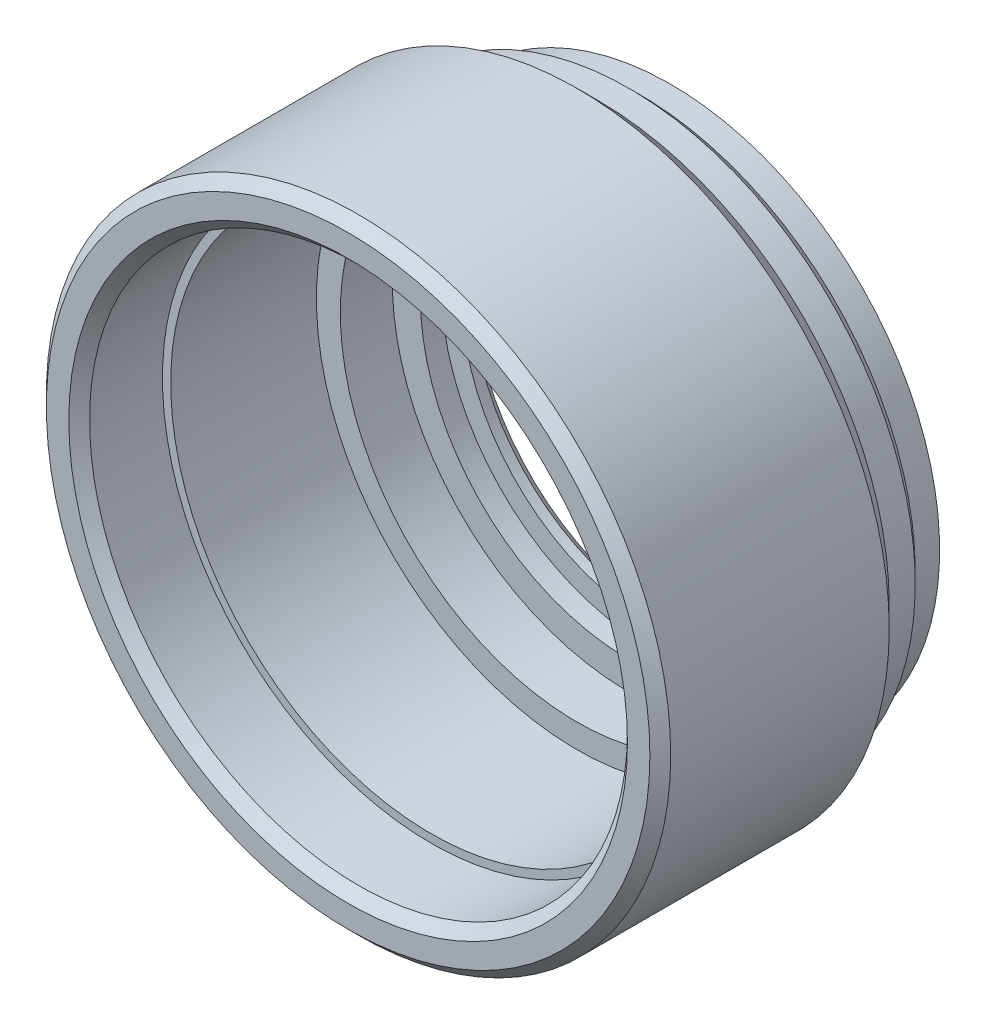
SolidWorks part; units mm, degrees
material "6061 Alloy"
ref_plane "Front Plane" through (0, 0, 0) normal (0, 0, 1) x (1, 0, 0)
ref_plane "Top Plane" through (0, 0, 0) normal (0, 1, 0) x (1, 0, 0)
ref_plane "Right Plane" through (0, 0, 0) normal (1, 0, 0) x (0, 0, -1)
sketch "Sketch1" plane through (0, 0, 0) normal (0, 0, 1) x (1, 0, 0)
  circle A0 centre (0, 0) radius 27.5
  dimension "D1" = 55
extrude "Boss-Extrude1" add sketch "Sketch1" along normal blind 7
sketch "Sketch4" plane through (0, 0, 7) normal (0, 0, 1) x (1, 0, 0)
  circle A0 centre (0, 0) radius 20.05
  dimension "D1" = 40.1
extrude "Cut-Extrude1" cut sketch "Sketch4" against normal offset from surface (5 mm away) 2 up to face at (27.5, 0, 0)
sketch "Sketch5" plane through (0, 0, 2) normal (0, 0, 1) x (1, 0, 0)
  circle A0 centre (0, 0) radius 18.05
  circle A1 centre (0, 0) radius 20.05 construction
  dimension "D1" = 2
extrude "Cut-Extrude2" cut sketch "Sketch5" against normal through all
sketch "Sketch6" plane through (0, 0, 7) normal (0, 0, 1) x (1, 0, 0)
  circle A0 centre (0, 0) radius 20.05
  circle A1 centre (0, 0) radius 30
  circle A2 centre (0, 0) radius 20.05 construction
  dimension "D1" = 60
extrude "Boss-Extrude2" add sketch "Sketch6" along normal blind 24
sketch "Sketch7" plane through (0, 0, 31) normal (0, 0, 1) x (1, 0, 0)
  circle A0 centre (0, 0) radius 25.05
  dimension "D1" = 50.1
extrude "Cut-Extrude3" cut sketch "Sketch7" against normal offset from surface (22 mm away) 2 up to face at (27.5, 0, 7)
sketch "Sketch8" plane through (0, 0, 9) normal (0, 0, 1) x (1, 0, 0)
  circle A0 centre (0, 0) radius 22.75
  dimension "D1" = 45.5
extrude "Cut-Extrude4" cut sketch "Sketch8" against normal blind 5
sketch "Sketch9" plane through (0, 0, 31) normal (0, 0, 1) x (1, 0, 0)
  circle A0 centre (0, 0) radius 25.8445
  dimension "D1" = 51.689
extrude "Cut-Extrude5" cut sketch "Sketch9" against normal blind 8
sketch "Sketch10" plane through (0, 0, 0) normal (0, 0, -1) x (-1, 0, 0)
  circle A0 centre (0, 0) radius 25.8445
  circle A1 centre (0, 0) radius 27.5 construction
  dimension "D1" = 51.689
extrude "Cut-Extrude6" cut sketch "Sketch10" against normal blind 3 flip side to cut
chamfer "Chamfer3" distance 2 angle 45 1 edges at (30, 0, 7)
chamfer "Chamfer4" distance 1 angle 45 1 edges at (-27.5, 0, 3)
chamfer "Chamfer5" distance 1 angle 45 3 edges at (25.8445, 0, 31) (30, 0, 31) (18.05, 0, 0)
